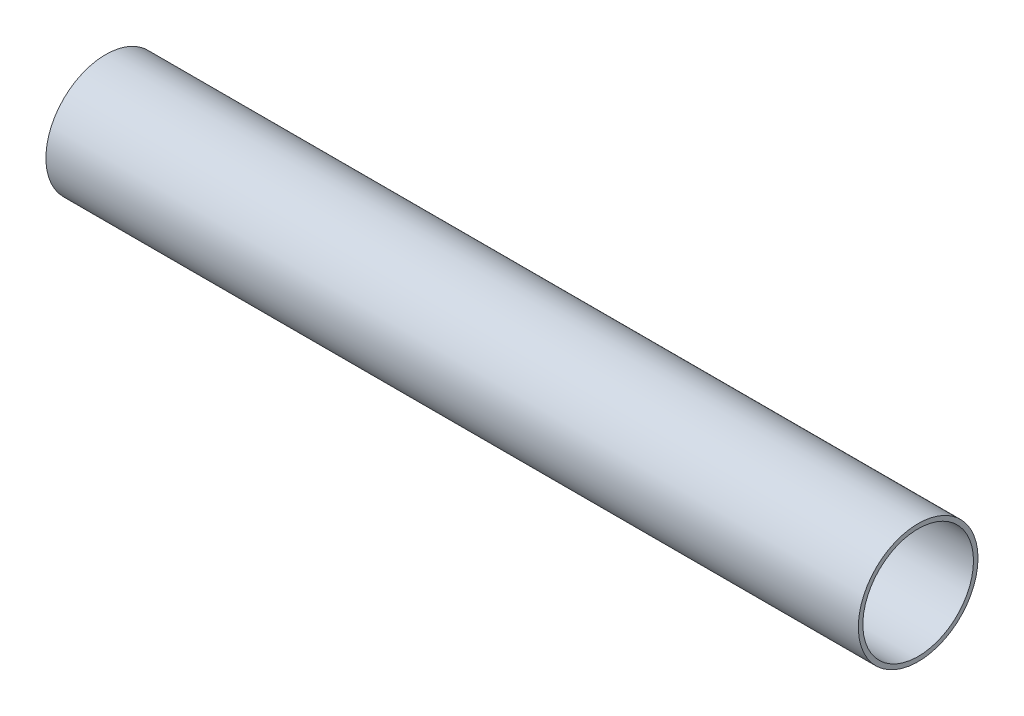
SolidWorks part; units mm, degrees
material "Silicon Rubber"
ref_plane "Front Plane" through (0, 0, 0) normal (0, 0, 1) x (1, 0, 0)
ref_plane "Top Plane" through (0, 0, 0) normal (0, 1, 0) x (1, 0, 0)
ref_plane "Right Plane" through (0, 0, 0) normal (1, 0, 0) x (0, 0, -1)
sketch "Sketch1" plane through (0, 0, 0) normal (1, 0, 0) x (0, 0, -1)
  circle A0 centre (0, 0) radius 15.875
  circle A1 centre (0, 0) radius 17.1714
  dimension "D1" = 31.75
  dimension "D2" = 34.3429
extrude "Boss-Extrude1" add sketch "Sketch1" along normal mid plane 233.1432
equation "\"D2@Sketch1\"=sqr((1.25)^2+(1.125)^2-1)"
